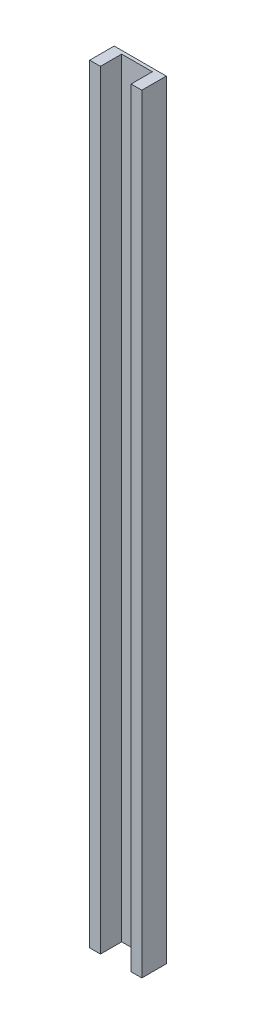
SolidWorks part; units mm, degrees
ref_plane "Plan de face" through (0, 0, 0) normal (0, 0, 1) x (1, 0, 0)
ref_plane "Plan de dessus" through (0, 0, 0) normal (0, 1, 0) x (1, 0, 0)
ref_plane "Plan de droite" through (0, 0, 0) normal (1, 0, 0) x (0, 0, -1)
sketch "Sketch1" plane through (0, 0, 0) normal (0, 1, 0) x (1, 0, 0)
  line L0 (-5, -4) -> (-5, 2.9388)
  line L1 (8.5, -4) -> (5, -4)
  line L2 (8.5, -4) -> (8.5, 4)
  line L3 (8.5, 4) -> (-8.5, 4)
  line L4 (-8.5, -4) -> (-8.5, 4)
  line L7 (-5, 2.9388) -> (5, 2.9388)
  line L8 (5, 2.9388) -> (5, -4)
  line L9 (-5, -4) -> (-8.5, -4)
  point P0 (0, 0)
  dimension "D1" = 17
  dimension "D2" = 8
  dimension "D3" = 10
  dimension "D4" = 3.5
extrude "Boss-Extrude1" add sketch "Sketch1" along normal blind 251
